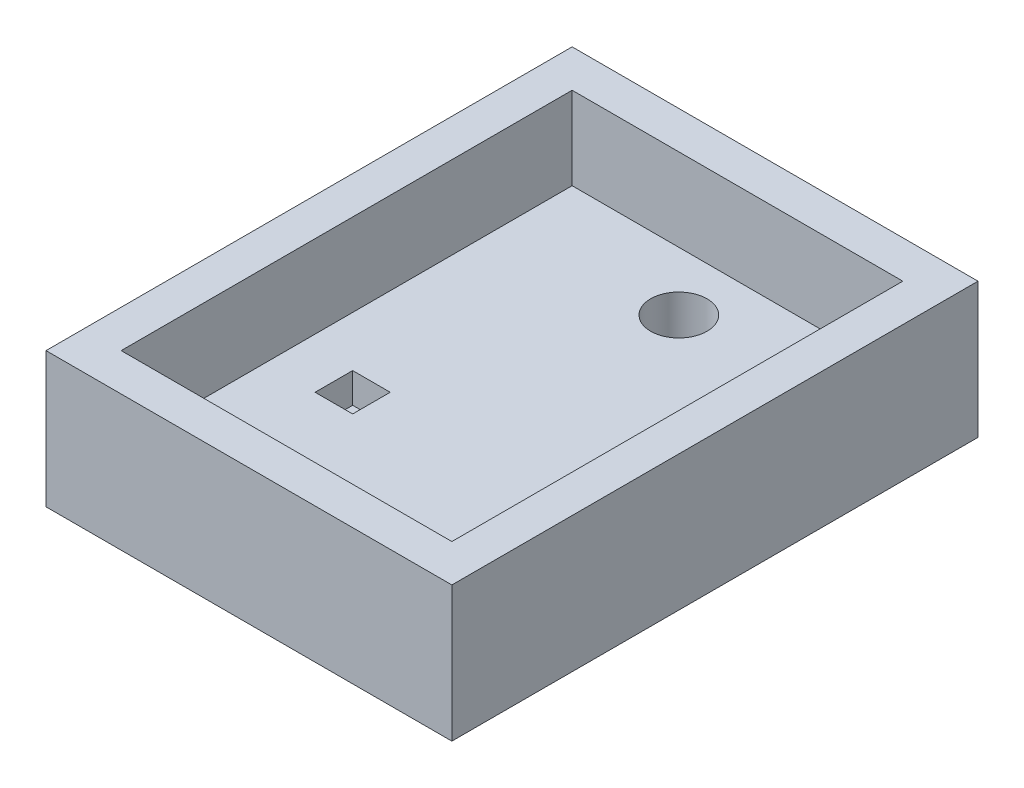
SolidWorks part; units mm, degrees
material "ABS"
ref_plane "Front Plane" through (0, 0, 0) normal (0, 0, 1) x (1, 0, 0)
ref_plane "Top Plane" through (0, 0, 0) normal (0, 1, 0) x (1, 0, 0)
ref_plane "Right Plane" through (0, 0, 0) normal (1, 0, 0) x (0, 0, -1)
sketch "Sketch1" plane through (0, 0, 0) normal (0, 1, 0) x (1, 0, 0)
  line L1 (0, 0) -> (68.58, 0)
  line L2 (0, 0) -> (0, 88.9)
  line L3 (0, 88.9) -> (68.58, 88.9)
  line L4 (68.58, 0) -> (68.58, 88.9)
  dimension "D1" = 88.9
  dimension "D2" = 68.58
extrude "Boss-Extrude1" add sketch "Sketch1" along normal blind 22.86
sketch "Sketch2" plane through (0, 22.86, 0) normal (0, 1, 0) x (1, 0, 0)
  line L0 (34.29, 88.9) -> (34.29, 0) construction
  line L1 (68.58, 88.9) -> (0, 88.9) construction
  line L2 (0, 0) -> (68.58, 0) construction
  line L3 (0, 44.45) -> (68.58, 44.45) construction
  line L4 (0, 88.9) -> (0, 0) construction
  line L5 (68.58, 0) -> (68.58, 88.9) construction
  line L7 (6.35, 6.35) -> (62.23, 6.35)
  line L8 (6.35, 6.35) -> (6.35, 82.55)
  line L9 (6.35, 82.55) -> (62.23, 82.55)
  line L10 (62.23, 6.35) -> (62.23, 82.55)
  line L11 (6.35, 6.35) -> (62.23, 82.55) construction
  line L12 (6.35, 82.55) -> (62.23, 6.35) construction
  point P12 (34.29, 44.45)
  dimension "D1" = 76.2
  dimension "D2" = 55.88
  dimension "D3" = 6.35
  dimension "D4" = 6.35
extrude "Cut-Extrude1" cut sketch "Sketch2" against normal offset from surface (13.97 mm away) 8.89 up to face at (34.29, 0, -44.45)
sketch "Sketch5" plane through (0, 8.89, 0) normal (0, 1, 0) x (1, 0, 0)
  line L0 (34.29, 82.55) -> (34.29, 6.35) construction
  line L1 (62.23, 82.55) -> (6.35, 82.55) construction
  line L2 (6.35, 6.35) -> (62.23, 6.35) construction
  line L3 (62.23, 44.45) -> (6.35, 44.45) construction
  line L4 (62.23, 6.35) -> (62.23, 82.55) construction
  line L5 (6.35, 82.55) -> (6.35, 6.35) construction
  circle A0 centre (34.29, 72.644) radius 4.7625
  dimension "D1" = 9.525
  dimension "D2" = 9.906
sketch "Sketch6" plane through (0, 8.89, 0) normal (0, 1, 0) x (1, 0, 0)
  line L0 (18.034, 16.891) -> (18.034, 10.541) construction
  line L1 (21.209, 36.957) -> (14.859, 36.957)
  line L2 (21.209, 36.957) -> (21.209, 30.607)
  line L3 (21.209, 30.607) -> (14.859, 30.607)
  line L4 (14.859, 36.957) -> (14.859, 30.607)
  line L5 (14.859, 16.891) -> (21.209, 16.891)
  line L6 (14.859, 16.891) -> (14.859, 10.541)
  line L7 (14.859, 10.541) -> (21.209, 10.541)
  line L8 (21.209, 16.891) -> (21.209, 10.541)
  line L9 (14.859, 13.716) -> (21.209, 13.716) construction
  line L10 (6.35, 82.55) -> (6.35, 6.35) construction
  line L11 (6.35, 6.35) -> (62.23, 6.35) construction
  dimension "D1" = 6.35
  dimension "D2" = 6.35
  dimension "D3" = 20.066
  dimension "D4" = 11.684
  dimension "D5" = 7.366
extrude "Cut-Extrude3" cut sketch "Sketch6" against normal blind 5.08
sketch "Sketch7" plane through (0, 3.81, 0) normal (0, 1, 0) x (1, 0, 0)
  line L0 (16.764, 13.716) -> (19.304, 13.716) construction
  line L1 (16.764, 32.512) -> (19.304, 32.512)
  line L2 (16.764, 32.512) -> (16.764, 35.052)
  line L3 (16.764, 35.052) -> (19.304, 35.052)
  line L4 (19.304, 32.512) -> (19.304, 35.052)
  line L5 (16.764, 12.446) -> (19.304, 12.446)
  line L6 (16.764, 12.446) -> (16.764, 14.986)
  line L7 (16.764, 14.986) -> (19.304, 14.986)
  line L8 (19.304, 12.446) -> (19.304, 14.986)
  line L9 (18.034, 12.446) -> (18.034, 14.986) construction
  line L10 (14.859, 16.891) -> (14.859, 10.541) construction
  line L11 (14.859, 10.541) -> (21.209, 10.541) construction
  dimension "D1" = 2.54
  dimension "D2" = 2.54
  dimension "D3" = 3.175
  dimension "D4" = 3.175
  dimension "D5" = 20.066
extrude "Cut-Extrude4" cut sketch "Sketch7" against normal through all
extrude "Cut-Extrude5" cut sketch "Sketch5" against normal through all
